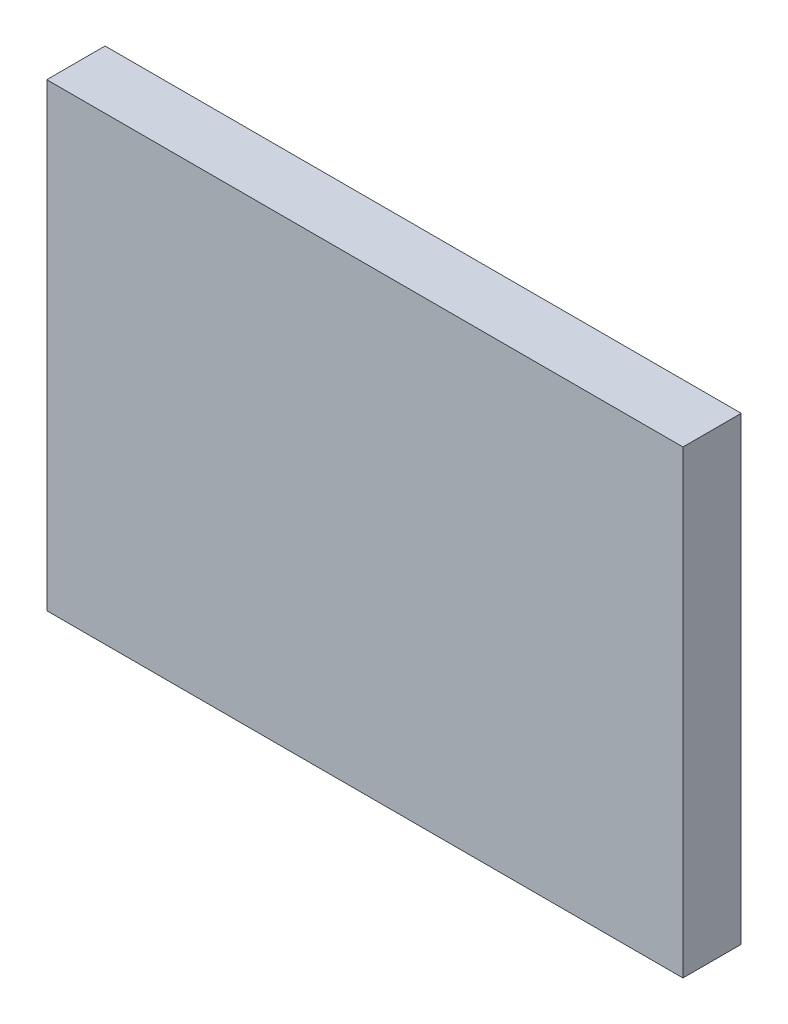
SolidWorks part; units mm, degrees
ref_plane "Ebene vorne" through (0, 0, 0) normal (0, 0, 1) x (1, 0, 0)
ref_plane "Ebene oben" through (0, 0, 0) normal (0, 1, 0) x (1, 0, 0)
ref_plane "Ebene rechts" through (0, 0, 0) normal (1, 0, 0) x (0, 0, -1)
sketch "Skizze1" plane through (0, 0, 0) normal (0, 0, 1) x (1, 0, 0)
  line L1 (6.912, 0) -> (0, 0)
  line L2 (6.912, 0) -> (6.912, 3.888)
  line L3 (6.912, 3.888) -> (0, 3.888)
  line L4 (0, 0) -> (0, 3.888)
  dimension "D1" = 6.912
  dimension "D2" = 3.888
extrude "Aufsatz-Linear austragen1" add sketch "Skizze1" along normal blind 1 contours L2 L1 L4 L3
sketch "Skizze2" plane through (0, 0, 1) normal (0, 0, 1) x (1, 0, 0)
  line L0 (6.912, 3.888) -> (0, 3.888) construction
  line L1 (-2, 5.888) -> (8.912, 5.888)
  line L2 (-2, 5.888) -> (-2, -2)
  line L3 (-2, -2) -> (8.912, -2)
  line L4 (8.912, 5.888) -> (8.912, -2)
  line L5 (6.912, 0) -> (6.912, 3.888) construction
  line L6 (6.912, 0) -> (0, 0) construction
  line L7 (0, 0) -> (0, 3.888) construction
  dimension "D1" = 2
  dimension "D2" = 2
  dimension "D3" = 2
  dimension "D4" = 2
extrude "Aufsatz-Linear austragen2" add sketch "Skizze2" along normal blind 1 contours L2 L1 L4 L3
sketch3d "3D-Skizze1"
  point P0 (3.0972, 2.5054, 0)
sketch "Skizze3" plane through (0, 0, 0) normal (0, 0, -1) x (-1, 0, 0)
  line L1 (-3.956, 2.444) -> (-2.956, 2.444)
  line L2 (-3.956, 2.444) -> (-3.956, 1.444)
  line L3 (-3.956, 1.444) -> (-2.956, 1.444)
  line L4 (-2.956, 2.444) -> (-2.956, 1.444)
  line L5 (-6.912, 0) -> (-6.912, 3.888) construction
  line L7 (0, 0) -> (0, 3.888) construction
  line L9 (-6.912, 0) -> (0, 0) construction
  line L10 (-3.456, 3.888) -> (-3.456, 0) construction
  line L11 (-6.912, 3.888) -> (0, 3.888) construction
  line L12 (-6.912, 0) -> (0, 0) construction
  line L13 (-6.912, 1.944) -> (0, 1.944) construction
  line L14 (0, 0) -> (0, 3.888) construction
  line L15 (-3.956, 2.444) -> (-2.956, 1.444) construction
  line L16 (-3.956, 1.444) -> (-2.956, 2.444) construction
  line L17 (-3.956, 1.944) -> (-3.456, 2.444)
  line L18 (-3.956, 1.944) -> (-3.4611, 1.4491)
  line L19 (-3.456, 2.444) -> (-2.9611, 1.9491)
  line L20 (-3.4611, 1.4491) -> (-2.9611, 1.9491)
  point P22 (-3.456, 1.944)
  point P23 (-3.456, 1.944)
  dimension "D1" = 1
  dimension "D2" = 1
  dimension "D3" = 0.7071
  dimension "D4" = 2.956
  dimension "D6" = 1.444
extrude "Aufsatz-Linear austragen3" add sketch "Skizze3" along normal blind 0.48 contours L17 L18 L20 L19
sketch "Skizze6" plane through (1.006, -1.006, 0) normal (0.7071, -0.7071, 0) x (0, 0, -1)
  line L0 (0, 4.1719) -> (0.48, 3.472) construction
  line L1 (0, 3.472) -> (0.48, 4.1719) construction
  line L2 (0.48, 4.1719) -> (0.24, 3.822)
  line L3 (0.24, 3.822) -> (0.48, 3.472)
  line L4 (0.48, 3.472) -> (0.48, 4.1719)
extrude "Schnitt-Linear austragen1" cut sketch "Skizze6" against normal blind 40.48
sketch "Skizze7" plane through (0.9436, 0.9436, -1.9459) normal (0.3999, 0.3999, -0.8247) x (-0.9166, 0.1745, -0.3598)
  line L0 (-3.0167, 1.4218) -> (-2.2012, 1.5443) construction
  circle A0 centre (-2.6089, 1.4831) radius 0.1
extrude "Schnitt-Linear austragen2" cut sketch "Skizze7" against normal blind 0.1
sketch "Skizze8" plane through (0.7853, 0.7853, 1.6194) normal (-0.3999, -0.3999, -0.8247) x (-0.9166, 0.1745, 0.3598)
  line L0 (-3.4594, 1.9586) -> (-2.6439, 2.0811) construction
  circle A0 centre (-3.0516, 2.0199) radius 0.1
extrude "Schnitt-Linear austragen3" cut sketch "Skizze8" against normal blind 0.1
